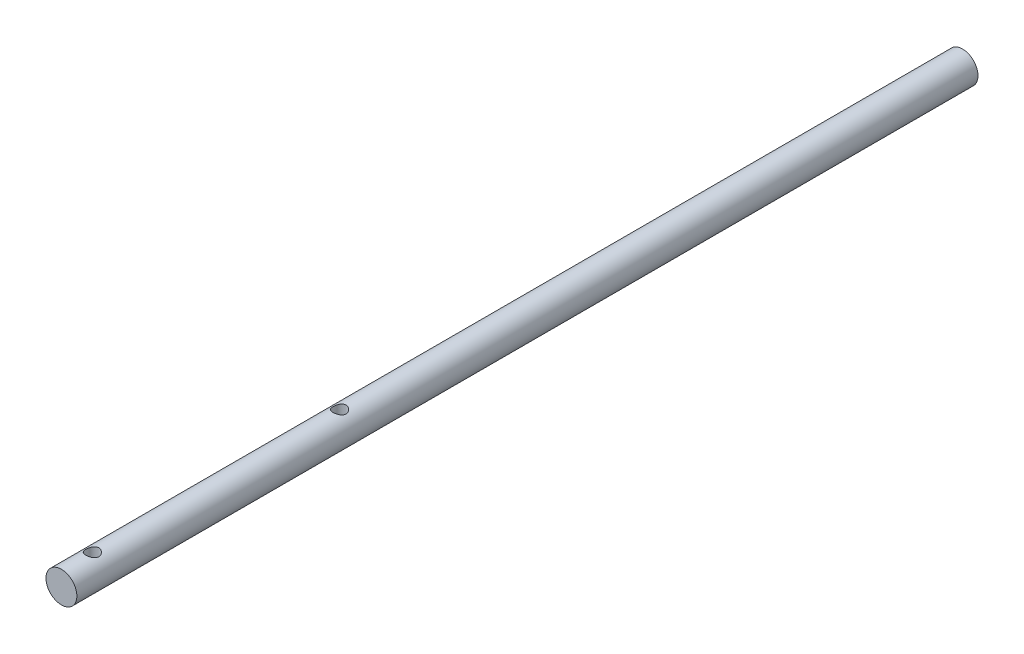
SolidWorks part; units mm, degrees
ref_plane "Plan de face" through (0, 0, 0) normal (0, 0, 1) x (1, 0, 0)
ref_plane "Plan de dessus" through (0, 0, 0) normal (0, 1, 0) x (1, 0, 0)
ref_plane "Plan de droite" through (0, 0, 0) normal (1, 0, 0) x (0, 0, -1)
sketch "Esquisse1" plane through (0, 0, 0) normal (0, 0, 1) x (1, 0, 0)
  circle A0 centre (0, 0) radius 3
  dimension "D1" = 6
extrude "Boss.-Extru.1" add sketch "Esquisse1" along normal blind 175
sketch "Esquisse2" plane through (0, 0, 0) normal (0, 1, 0) x (1, 0, 0)
  line L1 (-3, -175) -> (3, -175) construction
  circle A0 centre (0, -121) radius 1.25
  circle A1 centre (0, -169) radius 1.25
  dimension "D1" = 6
  dimension "D2" = 48
  dimension "D3" = 2.5
extrude "Enlèv. mat.-Extru.1" cut sketch "Esquisse2" against normal through all both and the other way through all
